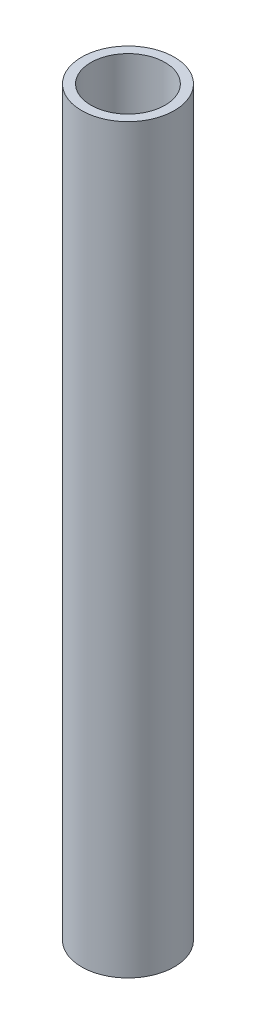
SolidWorks part; units mm, degrees
ref_plane "Front" through (0, 0, 0) normal (0, 0, 1) x (1, 0, 0)
ref_plane "Top" through (0, 0, 0) normal (0, 1, 0) x (1, 0, 0)
ref_plane "Right" through (0, 0, 0) normal (1, 0, 0) x (0, 0, -1)
sketch "Sketch1" plane through (0, 0, 0) normal (0, 1, 0) x (1, 0, 0)
  circle A0 centre (0, 0) radius 15.875
  circle A1 centre (0, 0) radius 12.7
  dimension "D1" = 31.75
  dimension "D2" = 3.175
extrude "Boss-Extrude1" add sketch "Sketch1" along normal mid plane 254
